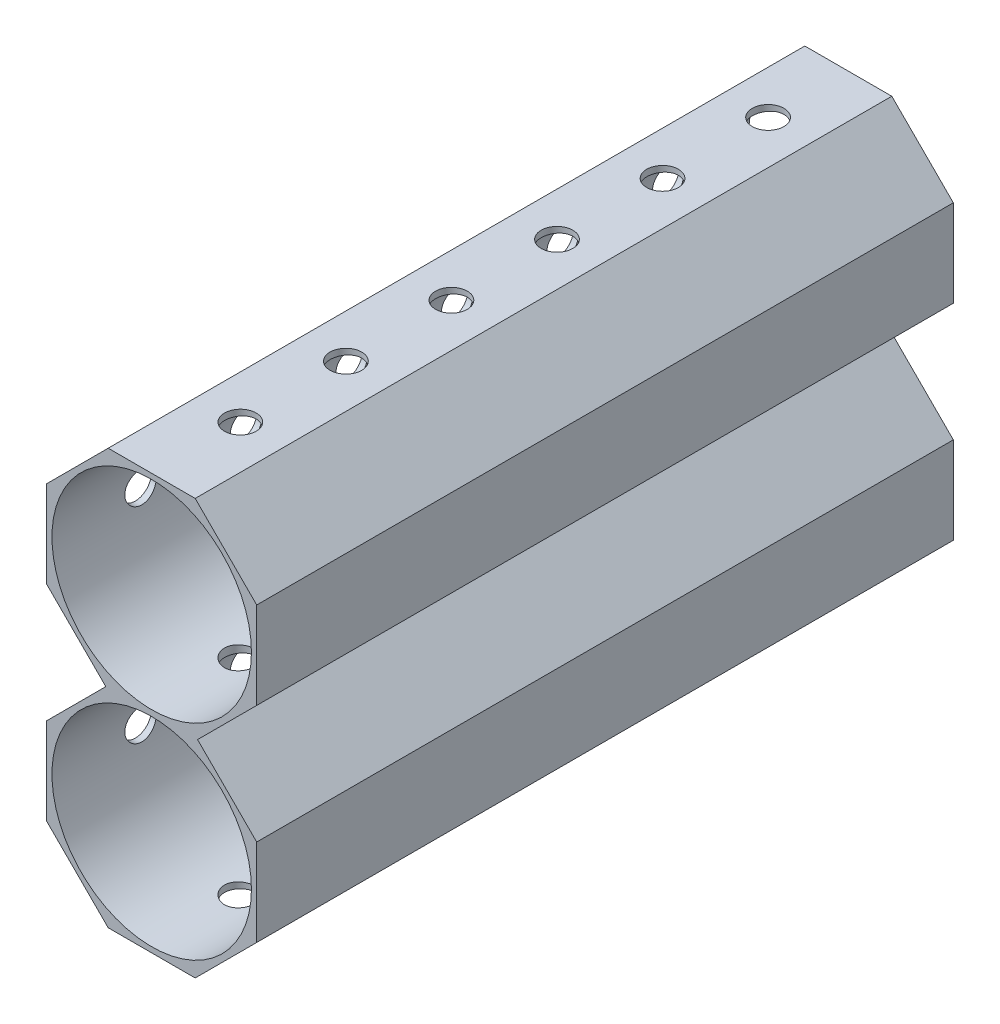
SolidWorks part; units mm, degrees
ref_plane "Ebene vorne" through (0, 0, 0) normal (1, 0, 0) x (0, 1, 0)
ref_plane "Ebene oben" through (0, 0, 0) normal (0, 0, 1) x (0, 1, 0)
ref_plane "Ebene rechts" through (0, 0, 0) normal (0, 1, 0) x (-1, 0, 0)
sketch "Skizze1" plane through (0, 0, 0) normal (0, 0, 1) x (0, 1, 0)
  line L13 (9.725, 4.3464) -> (4.1214, 9.95)
  line L14 (4.1214, 9.95) -> (-4.1214, 9.95)
  line L15 (-4.1214, 9.95) -> (-9.95, 4.1214)
  line L16 (-9.95, 4.1214) -> (-9.95, -4.1214)
  line L17 (-9.95, -4.1214) -> (-4.1214, -9.95)
  line L18 (-4.1214, -9.95) -> (4.1214, -9.95)
  line L19 (4.1214, -9.95) -> (9.725, -4.3464)
  line L21 (23.5714, 9.95) -> (15.3286, 9.95)
  line L22 (15.3286, 9.95) -> (9.725, 4.3464)
  line L24 (9.725, -4.3464) -> (15.3286, -9.95)
  line L25 (15.3286, -9.95) -> (23.5714, -9.95)
  line L26 (23.5714, -9.95) -> (29.4, -4.1214)
  line L27 (29.4, -4.1214) -> (29.4, 4.1214)
  line L28 (29.4, 4.1214) -> (23.5714, 9.95)
  line L29 (9.95, -4.1214) -> (9.95, 4.1214) [skipped]
  line L30 (9.5, 4.1214) -> (9.5, -4.1214) [skipped]
  circle A0 centre (0, 0) radius 9.45
  circle A1 centre (0, 0) radius 9.95 construction
  circle A2 centre (19.45, 0) radius 9.95 construction
  circle A3 centre (19.45, 0) radius 9.45
  point P4 (0, 0)
  point P15 (0, 0)
  point P16 (0, 0)
  point P19 (0, 0)
  dimension "D1" = 18.9
  dimension "D2" = 19.9
  dimension "D3" = 19.9
  dimension "D4" = 19.45
  dimension "D5" = 18.9
extrude "Aufsatz-Linear austragen1" add sketch "Skizze1" along normal blind 66
sketch "Skizze3" plane through (-9.95, 0, 0) normal (-1, 0, 0) x (0, -1, 0)
  line L0 (0, 66) -> (0, 0) construction
  line L1 (-4.1214, 66) -> (4.1214, 66) construction
  circle A0 centre (0, 57.6) radius 1.5
  circle A1 centre (0, 47.6) radius 1.5
  circle A2 centre (0, 37.6) radius 1.5
  circle A3 centre (0, 27.6) radius 1.5
  circle A4 centre (0, 17.6) radius 1.5
  circle A5 centre (0, 7.6) radius 1.5
  dimension "D1" = 3
  dimension "D3" = 8.4
  dimension "D2" = 6
sketch "Skizze4" plane through (-9.95, 0, 0) normal (-1, 0, 0) x (0, -1, 0)
  line L0 (-19.45, 66) -> (-19.45, 0) construction
  line L1 (-23.5714, 66) -> (-15.3286, 66) construction
  line L2 (-23.5714, 0) -> (-15.3286, 0) construction
  circle A0 centre (-19.45, 57.6) radius 1.5
  circle A1 centre (-19.45, 47.6) radius 1.5
  circle A2 centre (-19.45, 37.6) radius 1.5
  circle A3 centre (-19.45, 27.6) radius 1.5
  circle A4 centre (-19.45, 17.6) radius 1.5
  circle A5 centre (-19.45, 7.6) radius 1.5
  dimension "D1" = 3
  dimension "D2" = 8.4
  dimension "D3" = 6
extrude "Schnitt-Linear austragen3" cut sketch "Skizze3" against normal blind 1
extrude "Schnitt-Linear austragen4" cut sketch "Skizze4" against normal blind 1
sketch "Skizze6" plane through (-16.7607, 16.7607, 0) normal (-0.7071, 0.7071, 0) x (-0.7071, -0.7071, 0)
  line L0 (-13.7532, 66) -> (-13.7532, 0) construction
  line L1 (-17.8747, 66) -> (-9.6318, 66) construction
  line L2 (-17.8747, 0) -> (-9.6318, 0) construction
  circle A0 centre (-13.7532, 57.6) radius 1.5
  circle A1 centre (-13.7532, 47.6) radius 1.5
  circle A2 centre (-13.7532, 37.6) radius 1.5
  circle A3 centre (-13.7532, 27.6) radius 1.5
  circle A4 centre (-13.7532, 17.6) radius 1.5
  circle A5 centre (-13.7532, 7.6) radius 1.5
  dimension "D1" = 3
  dimension "D2" = 8.4
  dimension "D3" = 6
extrude "Schnitt-Linear austragen5" cut sketch "Skizze6" against normal through all
sketch "Skizze7" plane through (-7.0357, 7.0357, 0) normal (-0.7071, 0.7071, 0) x (-0.7071, -0.7071, 0)
  line L0 (0.1591, 66) -> (0, 0) construction
  line L1 (-3.8032, 66) -> (4.1214, 66) construction
  circle A0 centre (0.1389, 57.6) radius 1.5
  circle A1 centre (0.1147, 47.6) radius 1.5
  circle A2 centre (0.0906, 37.6001) radius 1.5
  circle A3 centre (0.0665, 27.6001) radius 1.5
  circle A4 centre (0.0424, 17.6001) radius 1.5
  circle A5 centre (0.0183, 7.6001) radius 1.5
  dimension "D1" = 3
  dimension "D2" = 8.4
  dimension "D3" = 6
extrude "Schnitt-Linear austragen6" cut sketch "Skizze7" against normal through all
sketch "Skizze8" plane through (0, 29.4, 0) normal (0, 1, 0) x (-1, 0, 0)
  line L0 (0, 66) -> (0, 0) construction
  line L1 (-4.1214, 66) -> (4.1214, 66) construction
  circle A0 centre (0, 57.6) radius 1.5
  circle A1 centre (0, 47.6) radius 1.5
  circle A2 centre (0, 37.6) radius 1.5
  circle A3 centre (0, 27.6) radius 1.5
  circle A4 centre (0, 17.6) radius 1.5
  circle A5 centre (0, 7.6) radius 1.5
  dimension "D1" = 3
  dimension "D2" = 8.4
  dimension "D3" = 6
extrude "Schnitt-Linear austragen7" cut sketch "Skizze8" against normal through all
